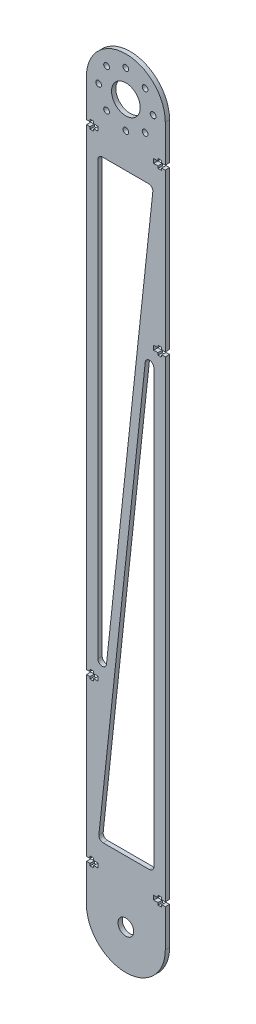
SolidWorks part; units mm, degrees
ref_plane "前视基准面" through (0, 0, 0) normal (0, 0, 1) x (1, 0, 0)
ref_plane "上视基准面" through (0, 0, 0) normal (0, 1, 0) x (1, 0, 0)
ref_plane "右视基准面" through (0, 0, 0) normal (1, 0, 0) x (0, 0, -1)
sketch "草图1" plane through (0, 0, 0) normal (0, 0, 1) x (1, 0, 0)
  line L50 (249.9534, 275.9629) -> (249.9534, 255.9629) construction
  line L71 (269.9534, 275.9629) -> (249.9534, 275.9629) construction
  line L261 (249.9534, 275.9629) -> (249.9534, -224.0371) construction
  line L262 (277.4534, 275.9629) -> (277.4534, -224.0371) construction
  line L263 (222.4534, -224.0371) -> (222.4534, 275.9629) construction
  line L264 (272.4534, 235.9629) -> (272.4534, -184.0371) construction
  line L265 (272.4534, -184.0371) -> (227.4534, -184.0371) construction
  line L266 (227.4534, -184.0371) -> (227.4534, 235.9629) construction
  line L267 (227.4534, 235.9629) -> (272.4534, 235.9629) construction
  line L268 (272.4534, 235.9629) -> (227.4534, -184.0371) construction
  line L270 (233.4534, 232.9629) -> (265.7762, 232.9629)
  line L271 (268.7591, 229.6433) -> (236.4363, -72.0362)
  line L272 (230.4534, -71.7166) -> (230.4534, 229.9629)
  line L273 (269.4534, 123.6424) -> (269.4534, -178.0371)
  line L274 (266.4534, -181.0371) -> (234.1306, -181.0371)
  line L275 (263.4704, 123.962) -> (231.1476, -177.7175)
  line L276 (269.4534, 179.8027) -> (269.4534, -181.0371) construction
  line L277 (269.4534, -181.0371) -> (230.792, -181.0371) construction
  line L278 (269.4534, 179.8027) -> (230.792, -181.0371) construction
  line L279 (230.4534, -127.8768) -> (230.4534, 232.9629) construction
  line L280 (269.1148, 232.9629) -> (230.4534, -127.8768) construction
  line L281 (230.4534, 232.9629) -> (269.1148, 232.9629) construction
  line L282 (224.9534, -85.2166) -> (224.9534, -86.7166)
  line L283 (224.9534, -82.2166) -> (224.9534, -80.7166)
  line L284 (222.4534, -82.2166) -> (224.9534, -82.2166)
  line L285 (224.9534, -86.7166) -> (227.5534, -86.7166)
  line L286 (227.5534, -86.7166) -> (227.5534, -85.2166)
  line L287 (227.5534, -85.2166) -> (230.5534, -85.2166)
  line L288 (230.5534, -82.2166) -> (230.5534, -85.2166)
  line L289 (227.5534, -82.2166) -> (230.5534, -82.2166)
  line L290 (227.5534, -80.7166) -> (227.5534, -82.2166)
  line L291 (224.9534, -80.7166) -> (227.5534, -80.7166)
  line L292 (224.9534, -85.2166) -> (222.4534, -85.2166)
  line L293 (230.5534, -83.7166) -> (222.4534, -83.7166) construction
  line L294 (233.4534, -71.7166) -> (233.4534, -83.7166) construction
  line L295 (233.4534, -83.7166) -> (222.4534, -83.7166) construction
  line L296 (249.9534, -196.5371) -> (222.4534, -196.5371) construction
  line L297 (249.9534, 248.4629) -> (222.4534, 248.4629) construction
  line L298 (224.9534, -198.0371) -> (224.9534, -199.5371)
  line L299 (224.9534, -195.0371) -> (224.9534, -193.5371)
  line L300 (222.4534, -195.0371) -> (224.9534, -195.0371)
  line L301 (224.9534, -199.5371) -> (227.5534, -199.5371)
  line L302 (227.5534, -199.5371) -> (227.5534, -198.0371)
  line L303 (227.5534, -198.0371) -> (230.5534, -198.0371)
  line L304 (230.5534, -195.0371) -> (230.5534, -198.0371)
  line L305 (227.5534, -195.0371) -> (230.5534, -195.0371)
  line L306 (227.5534, -193.5371) -> (227.5534, -195.0371)
  line L307 (224.9534, -193.5371) -> (227.5534, -193.5371)
  line L308 (224.9534, -198.0371) -> (222.4534, -198.0371)
  line L309 (230.5534, -196.5371) -> (222.4534, -196.5371) construction
  line L310 (224.9534, 246.9629) -> (224.9534, 245.4629)
  line L311 (224.9534, 249.9629) -> (224.9534, 251.4629)
  line L312 (222.4534, 249.9629) -> (224.9534, 249.9629)
  line L313 (224.9534, 245.4629) -> (227.5534, 245.4629)
  line L314 (227.5534, 245.4629) -> (227.5534, 246.9629)
  line L315 (227.5534, 246.9629) -> (230.5534, 246.9629)
  line L316 (230.5534, 249.9629) -> (230.5534, 246.9629)
  line L317 (227.5534, 249.9629) -> (230.5534, 249.9629)
  line L318 (227.5534, 251.4629) -> (227.5534, 249.9629)
  line L319 (224.9534, 251.4629) -> (227.5534, 251.4629)
  line L320 (224.9534, 246.9629) -> (222.4534, 246.9629)
  line L321 (230.5534, 248.4629) -> (222.4534, 248.4629) construction
  line L322 (222.4534, -85.2166) -> (222.4534, -195.0371)
  line L323 (222.4534, -198.0371) -> (222.4534, -224.0371)
  line L324 (222.4534, 246.9629) -> (222.4534, -82.2166)
  line L325 (222.4534, 275.9629) -> (222.4534, 249.9629)
  line L326 (277.4534, -195.0371) -> (274.9534, -195.0371)
  line L327 (274.9534, -195.0371) -> (274.9534, -193.5371)
  line L328 (274.9534, -193.5371) -> (272.3534, -193.5371)
  line L329 (272.3534, -193.5371) -> (272.3534, -195.0371)
  line L330 (272.3534, -195.0371) -> (269.3534, -195.0371)
  line L331 (269.3534, -195.0371) -> (269.3534, -198.0371)
  line L332 (272.3534, -198.0371) -> (269.3534, -198.0371)
  line L333 (274.9534, -199.5371) -> (272.3534, -199.5371)
  line L334 (272.3534, -199.5371) -> (272.3534, -198.0371)
  line L335 (274.9534, -198.0371) -> (274.9534, -199.5371)
  line L336 (274.9534, -198.0371) -> (277.4534, -198.0371)
  line L337 (272.3534, 249.9629) -> (269.3534, 249.9629)
  line L338 (269.3534, 249.9629) -> (269.3534, 246.9629)
  line L339 (272.3534, 246.9629) -> (269.3534, 246.9629)
  line L340 (272.3534, 245.4629) -> (272.3534, 246.9629)
  line L341 (274.9534, 245.4629) -> (272.3534, 245.4629)
  line L342 (274.9534, 246.9629) -> (274.9534, 245.4629)
  line L343 (274.9534, 246.9629) -> (277.4534, 246.9629)
  line L344 (277.4534, 249.9629) -> (274.9534, 249.9629)
  line L345 (274.9534, 249.9629) -> (274.9534, 251.4629)
  line L346 (274.9534, 251.4629) -> (272.3534, 251.4629)
  line L347 (272.3534, 251.4629) -> (272.3534, 249.9629)
  line L348 (266.4534, 123.6424) -> (266.4534, 135.6424) construction
  line L349 (274.9534, 137.1424) -> (274.9534, 138.6424)
  line L350 (274.9534, 134.1424) -> (274.9534, 132.6424)
  line L351 (277.4534, 134.1424) -> (274.9534, 134.1424)
  line L352 (274.9534, 138.6424) -> (272.3534, 138.6424)
  line L353 (272.3534, 138.6424) -> (272.3534, 137.1424)
  line L354 (272.3534, 137.1424) -> (269.3534, 137.1424)
  line L355 (269.3534, 134.1424) -> (269.3534, 137.1424)
  line L356 (272.3534, 134.1424) -> (269.3534, 134.1424)
  line L357 (272.3534, 132.6424) -> (272.3534, 134.1424)
  line L358 (274.9534, 132.6424) -> (272.3534, 132.6424)
  line L359 (274.9534, 137.1424) -> (277.4534, 137.1424)
  line L360 (269.3534, 135.6424) -> (277.4534, 135.6424) construction
  line L361 (266.4534, 135.6424) -> (277.4534, 135.6424) construction
  line L362 (277.4534, 275.9629) -> (277.4534, 249.9629)
  line L363 (277.4534, 246.9629) -> (277.4534, 137.1424)
  line L364 (277.4534, 134.1424) -> (277.4534, -195.0371)
  line L365 (277.4534, -198.0371) -> (277.4534, -224.0371)
  circle A14 centre (249.9534, 275.9629) radius 10
  circle A15 centre (249.9534, 275.9629) radius 19 construction
  circle A16 centre (230.9534, 275.9629) radius 2
  circle A17 centre (236.5183, 289.398) radius 2
  circle A18 centre (249.9534, 294.9629) radius 2
  circle A19 centre (263.3884, 289.398) radius 2
  circle A20 centre (268.9534, 275.9629) radius 2
  circle A21 centre (263.3884, 262.5279) radius 2
  circle A22 centre (249.9534, 256.9629) radius 2
  circle A23 centre (236.5183, 262.5279) radius 2
  circle A24 centre (249.9534, 275.9629) radius 27.5 construction
  circle A25 centre (249.9534, -224.0371) radius 27.5 construction
  arc A26 (277.4534, 275.9629) -> (222.4534, 275.9629) centre (249.9534, 275.9629) ccw
  arc A27 (277.4534, -224.0371) -> (222.4534, -224.0371) centre (249.9534, -224.0371) cw
  circle A28 centre (249.9534, -224.0371) radius 5.5
  arc A29 (269.4534, -178.0371) -> (266.4534, -181.0371) centre (266.4534, -178.0371) cw
  arc A30 (234.1306, -181.0371) -> (231.1476, -177.7175) centre (234.1306, -178.0371) cw
  arc A31 (269.4534, 123.6424) -> (263.4704, 123.962) centre (266.4534, 123.6424) ccw
  arc A32 (230.4534, -71.7166) -> (236.4363, -72.0362) centre (233.4534, -71.7166) ccw
  arc A33 (230.4534, 229.9629) -> (233.4534, 232.9629) centre (233.4534, 229.9629) cw
  arc A34 (268.7591, 229.6433) -> (265.7762, 232.9629) centre (265.7762, 229.9629) ccw
  dimension "D1" = 8
  dimension "D3" = 5
  dimension "D5" = 40
  dimension "D4" = 5
  dimension "D6" = 40
  dimension "D7" = 3
  dimension "D2" = 20
extrude "凸台-拉伸1" add sketch "草图1" along normal blind 3
sketch "草图2" plane through (277.4534, 0, 0) normal (1, 0, 0) x (0, 0, -1)
  line L0 (-1.5, 249.9629) -> (-1.5, 246.9629) construction
  line L1 (-3, 249.9629) -> (0, 249.9629) construction
  line L2 (-3, 246.9629) -> (0, 246.9629) construction
  circle A0 centre (-1.5, 248.4629) radius 1.5
sketch "草图3" plane through (222.4534, 0, 0) normal (-1, 0, 0) x (0, 0, 1)
  line L0 (1.5, -198.0371) -> (1.5, -195.0371)
  line L1 (3, -198.0371) -> (0, -198.0371) construction
  line L2 (3, -195.0371) -> (0, -195.0371) construction
  circle A0 centre (1.5, -196.5371) radius 1.5
